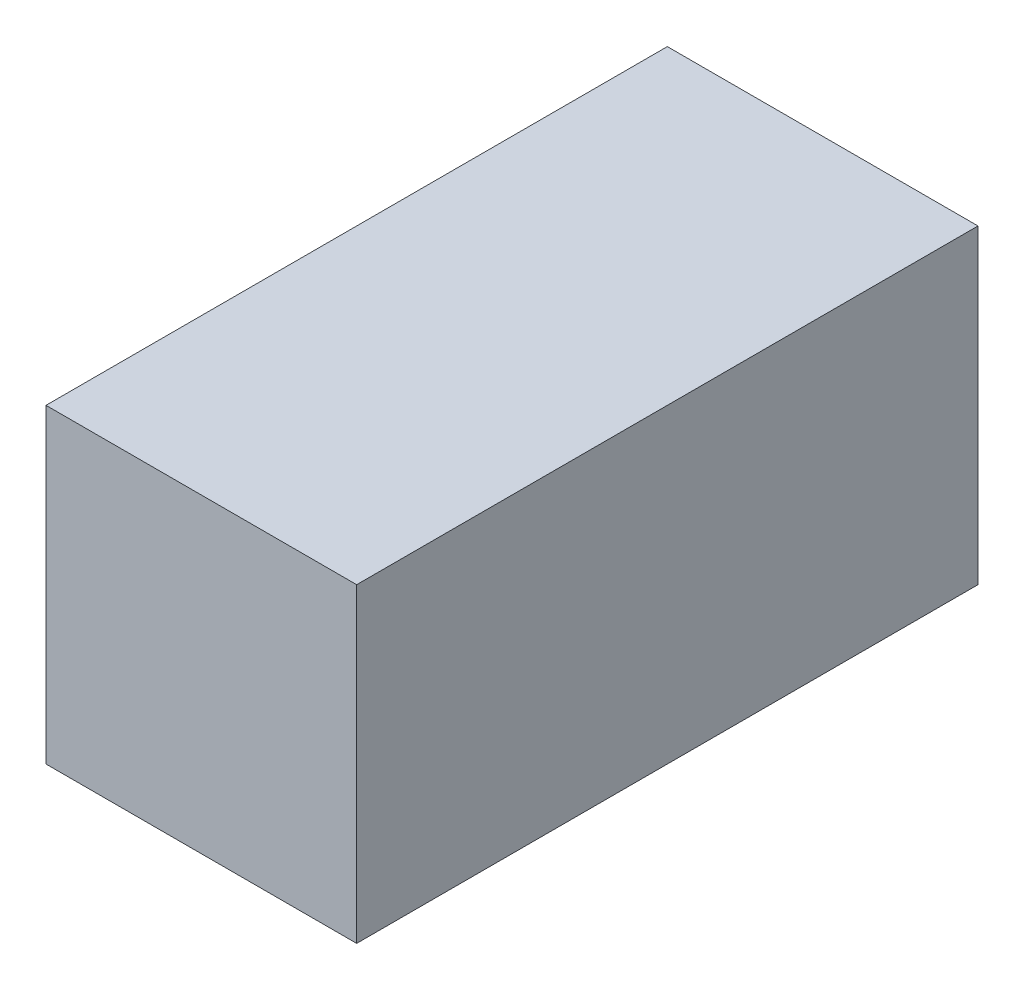
SolidWorks part; units mm, degrees
ref_plane "Plano frontal" through (0, 0, 0) normal (0, 0, 1) x (1, 0, 0)
ref_plane "Plano superior" through (0, 0, 0) normal (0, 1, 0) x (1, 0, 0)
ref_plane "Plano direito" through (0, 0, 0) normal (1, 0, 0) x (0, 0, -1)
sketch "Esboço1" plane through (0, 0, 0) normal (0, 0, 1) x (1, 0, 0)
  line L1 (0, 0) -> (5, 0)
  line L2 (0, 0) -> (0, 5)
  line L3 (0, 5) -> (5, 5)
  line L4 (5, 0) -> (5, 5)
  dimension "D1" = 5
  dimension "D2" = 5
extrude "Extrusão1" add sketch "Esboço1" along normal blind 10
